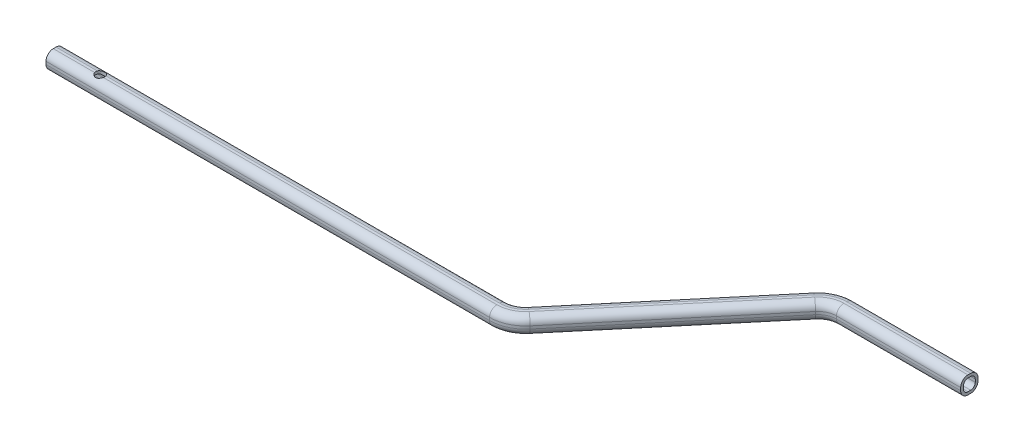
SolidWorks part; units mm, degrees
material "5052-H38, Rod (SS)"
ref_plane "Front Plane" through (0, 0, 0) normal (0, 0, 1) x (1, 0, 0)
ref_plane "Top Plane" through (0, 0, 0) normal (0, 1, 0) x (1, 0, 0)
ref_plane "Right Plane" through (0, 0, 0) normal (1, 0, 0) x (0, 0, -1)
sketch "Sketch2" plane through (0, 0, 0) normal (1, 0, 0) x (0, 0, -1)
  line L1 (-1.5, -6.5) -> (1.5, -6.5)
  line L2 (-6.5, -1.5) -> (-6.5, 1.5)
  line L3 (-1.5, 6.5) -> (1.5, 6.5)
  line L4 (6.5, -1.5) -> (6.5, 1.5)
  line L5 (-6.5, -6.5) -> (6.5, 6.5) construction
  line L6 (-6.5, 6.5) -> (6.5, -6.5) construction
  arc A0 (6.5, -1.5) -> (1.5, -6.5) centre (1.5, -1.5) cw
  arc A1 (-1.5, -6.5) -> (-6.5, -1.5) centre (-1.5, -1.5) cw
  arc A2 (-6.5, 1.5) -> (-1.5, 6.5) centre (-1.5, 1.5) cw
  arc A3 (1.5, 6.5) -> (6.5, 1.5) centre (1.5, 1.5) cw
  point P0 (0, 0)
  dimension "D3" = 5
  dimension "D1" = 13
  dimension "D2" = 13
sketch3d "3DSketch2"
  line L0 (508.9921, 0, -10.7164) -> (651.7048, 0, -180.7947)
  line L1 (674.6861, 0, -191.5111) -> (810.6969, 0, -191.5111)
  line L3 (0, 0, 0) -> (486.0108, 0, 0)
  line L4 (500, 0, 0) -> (628.2254, 0, 0) construction
  arc A0 (651.7048, 0, -180.7947) -> (674.6861, 0, -191.5111) centre (674.6861, 0, -161.5111) ccw
  arc A1 (486.0108, 0, 0) -> (508.9921, 0, -10.7164) centre (486.0108, 0, -30) ccw
  point P9 (660.6969, 0, -191.5111)
  point P10 (674.6861, -30, -161.5111)
  point P13 (500, 0, 0)
  point P15 (486.0108, 30, -30)
  dimension "D5" = 30
  dimension "D6" = 30
  dimension "D1" = 500
  dimension "D2" = 250
  dimension "D3" = 130
  dimension "D4" = 150
sweep "Sweep-Thin3" add profiles "Sketch2" path "3DSketch2" parameters "D1"=3
sketch "Sketch21" plane through (0, 0, 0) normal (0, 1, 0) x (1, 0, 0)
  line L0 (0, 0) -> (486.0108, 0) construction
  circle A0 centre (50, 0) radius 5
  dimension "D1" = 10
  dimension "D2" = 50
extrude "Cut-Extrude3" cut sketch "Sketch21" against normal through all both and the other way through all
sketch "Sketch22" [suppressed] plane through (0, 0, 0) normal (0, 0, 1) x (1, 0, 0)
ref_plane "Plane1" [suppressed] through (0, -210, 0) normal (0, 1, 0) x (1, 0, 0)
